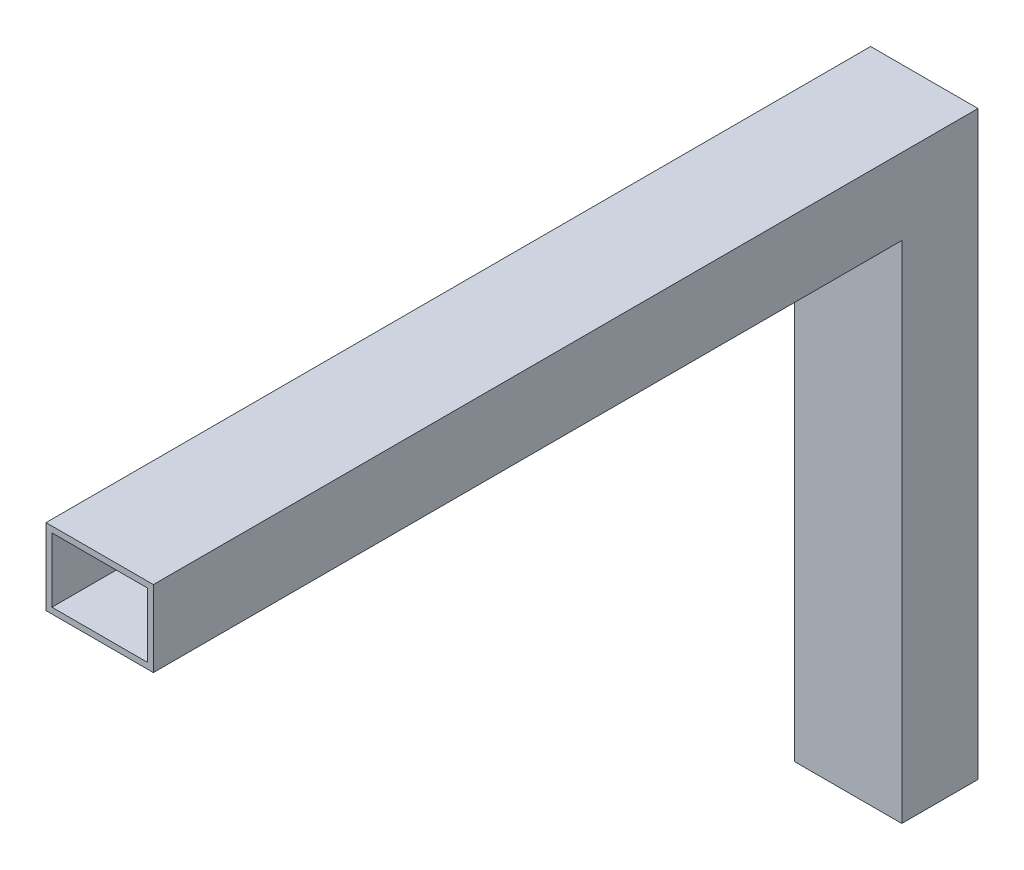
SolidWorks part; units mm, degrees
ref_plane "Front Plane" through (0, 0, 0) normal (0, 0, 1) x (1, 0, 0)
ref_plane "Top Plane" through (0, 0, 0) normal (0, 1, 0) x (1, 0, 0)
ref_plane "Right Plane" through (0, 0, 0) normal (1, 0, 0) x (0, 0, -1)
sketch "Sketch1" plane through (0, 0, 0) normal (1, 0, 0) x (0, 0, -1)
  line L0 (-59.9082, 20.9401) -> (6.3791, 20.9401)
  line L1 (6.3791, 20.9401) -> (6.3791, -24.8231)
sketch "Sketch2" plane through (0, 20.9401, 59.9082) normal (0, 0, -1) x (-1, 0, 0)
  line L1 (4.5252, 3.2129) -> (-4.5252, 3.2129)
  line L2 (4.5252, 3.2129) -> (4.5252, -3.2129)
  line L3 (4.5252, -3.2129) -> (-4.5252, -3.2129)
  line L4 (-4.5252, 3.2129) -> (-4.5252, -3.2129)
  line L5 (4.5252, 3.2129) -> (-4.5252, -3.2129) construction
  line L6 (4.5252, -3.2129) -> (-4.5252, 3.2129) construction
  point P0 (0, 0)
sweep "Sweep-Thin1" add profiles "Sketch2" path "Sketch1" parameters "D1"=0.5
